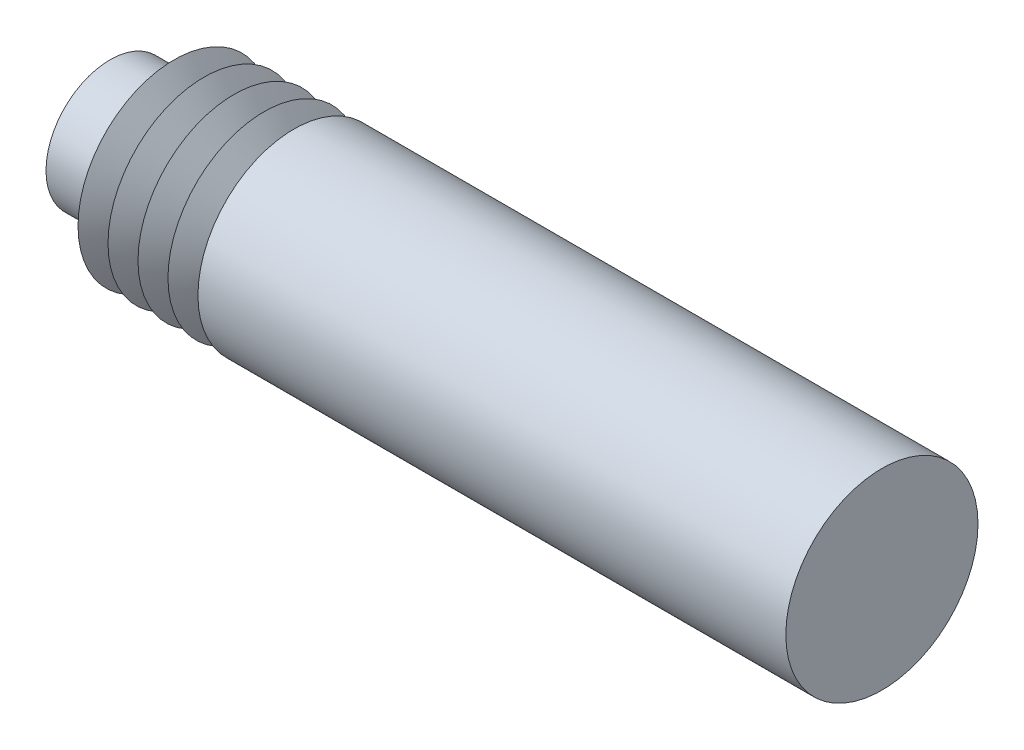
SolidWorks part; units mm, degrees
ref_plane "Plano frontal" through (0, 0, 0) normal (0, 0, 1) x (1, 0, 0)
ref_plane "Plano superior" through (0, 0, 0) normal (0, 1, 0) x (1, 0, 0)
ref_plane "Plano direito" through (0, 0, 0) normal (1, 0, 0) x (0, 0, -1)
sketch "Esboço1" plane through (0, 0, 0) normal (0, 0, 1) x (1, 0, 0)
  line L0 (-15.245, 0) -> (-15.245, 2.5)
  line L1 (-30.125, 2.5) -> (-30.125, 5)
  line L2 (30.125, 7.5) -> (30.125, 0)
  line L3 (-30.125, 5) -> (-25.125, 5)
  line L4 (-25.125, 5) -> (-25.125, 7.5)
  line L5 (-15.765, 7.5) -> (30.125, 7.5)
  line L6 (0, 0) -> (62.7162, 0) construction
  line L7 (30.125, 0) -> (-15.245, 0)
  line L8 (-15.245, 2.5) -> (-30.125, 2.5)
  line L10 (-22.785, 7.5) -> (-21.615, 5.7)
  line L11 (-25.125, 7.5) -> (-23.955, 5.7)
  line L12 (-23.955, 5.7) -> (-22.785, 7.5)
  line L13 (-21.615, 5.7) -> (-20.445, 7.5)
  line L14 (-20.445, 7.5) -> (-19.275, 5.7)
  line L15 (-19.275, 5.7) -> (-18.105, 7.5)
  line L16 (-18.105, 7.5) -> (-16.935, 5.7)
  line L17 (-16.935, 5.7) -> (-15.765, 7.5)
  point P4 (0, 0)
  point P6 (0, 0)
  point P10 (0, 0)
  point P14 (0, 0)
  point P23 (0, 0)
  point P24 (0, 0)
  point P25 (0, 0)
  point P26 (0, 0)
  point P27 (0, 0)
  point P28 (0, 0)
  point P29 (0, 0)
  point P30 (0, 0)
  dimension "D1" = 2.5
  dimension "D2" = 2.5
  dimension "D3" = 7.5
  dimension "D4" = 5
  dimension "D5" = 14.88
  dimension "D6" = 60.25
  dimension "D7" = 2.34
  dimension "D8" = 1.17
  dimension "D9" = 1.8
  dimension "D10" = 45.89
  dimension "D11" = 1.17
  dimension "D12" = 2.34
  dimension "D13" = 1.17
  dimension "D14" = 1.17
  dimension "D15" = 1.17
  dimension "D16" = 30.125
  dimension "D17" = 45.37
  dimension "D18" = 7.5
revolve "Revolução1" add sketch "Esboço1" angle 360 about L6
